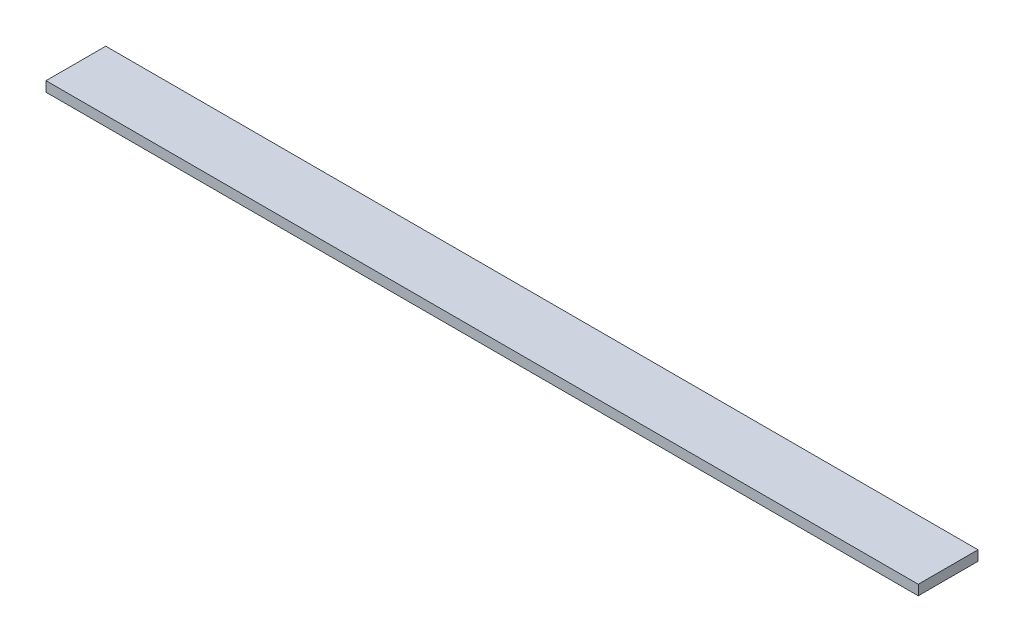
SolidWorks part; units mm, degrees
ref_plane "Front Plane" through (0, 0, 0) normal (0, 0, 1) x (1, 0, 0)
ref_plane "Top Plane" through (0, 0, 0) normal (0, 1, 0) x (1, 0, 0)
ref_plane "Right Plane" through (0, 0, 0) normal (1, 0, 0) x (0, 0, -1)
sketch "Sketch1" plane through (0, 0, 0) normal (1, 0, 0) x (0, 0, -1)
  line L1 (-68.5, -11.5) -> (68.5, -11.5)
  line L2 (-68.5, -11.5) -> (-68.5, 11.5)
  line L3 (-68.5, 11.5) -> (68.5, 11.5)
  line L4 (68.5, -11.5) -> (68.5, 11.5)
  line L5 (-68.5, -11.5) -> (68.5, 11.5) construction
  line L6 (-68.5, 11.5) -> (68.5, -11.5) construction
  point P0 (0, 0)
  dimension "D1" = 137
  dimension "D2" = 23
extrude "Boss-Extrude1" add sketch "Sketch1" along normal blind 2000
